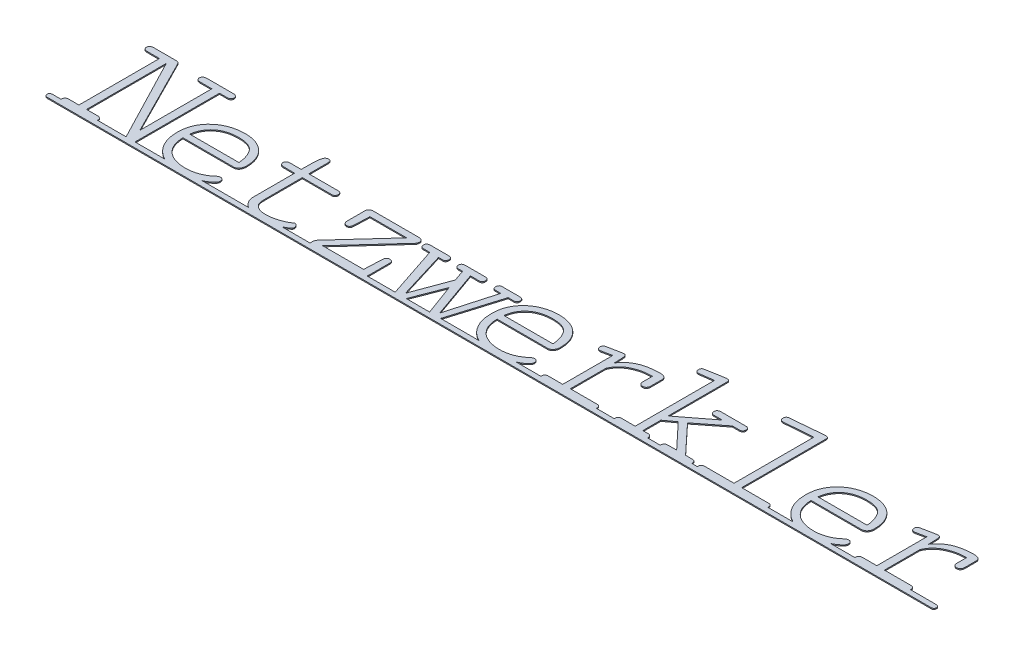
SolidWorks part; units mm, degrees
ref_plane "Vorderansicht" through (0, 0, 0) normal (0, 0, 1) x (1, 0, 0)
ref_plane "Draufsicht" through (0, 0, 0) normal (0, 1, 0) x (1, 0, 0)
ref_plane "Seitenansicht" through (0, 0, 0) normal (1, 0, 0) x (0, 0, -1)
sketch "Skizze2" plane through (0, 0, 0) normal (0, 1, 0) x (1, 0, 0)
  text T0 "Netzwerkler" font "Cutive Mono" height 90
  point P1 (0, 0)
extrude "Aufsatz-Linear austragen1" add sketch "Skizze2" along normal blind 1
sketch "Skizze4" plane through (0, 0, 0) normal (0, 1, 0) x (1, 0, 0)
  line L0 (0, 0) -> (850, 0) construction
  line L1 (0, 2.5) -> (850, 2.5)
  line L2 (0, -2.5) -> (850, -2.5)
  arc A0 (0, 2.5) -> (0, -2.5) centre (0, 0) ccw
  arc A1 (850, -2.5) -> (850, 2.5) centre (850, 0) ccw
  point P2 (425, 0)
  dimension "D1" = 5
  dimension "D2" = 850
  dimension "D3" = 0
  dimension "D4" = 0
extrude "Aufsatz-Linear austragen3" add sketch "Skizze4" along normal blind 1
